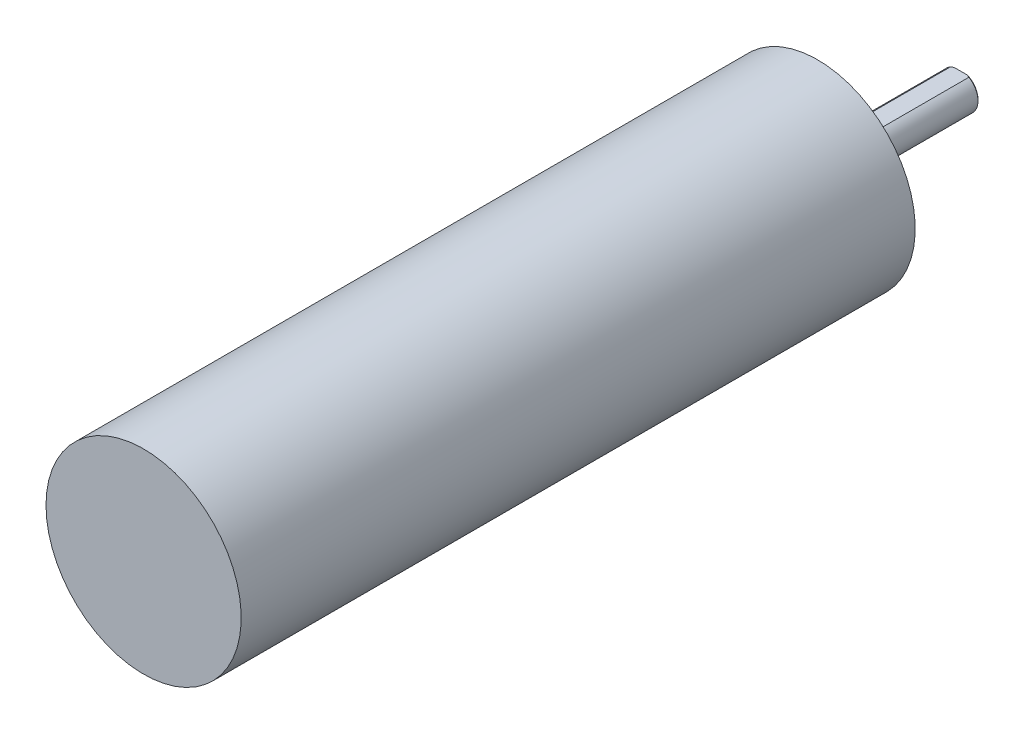
SolidWorks part; units mm, degrees
ref_plane "前视基准面" through (0, 0, 0) normal (0, 0, 1) x (1, 0, 0)
ref_plane "上视基准面" through (0, 0, 0) normal (0, 1, 0) x (1, 0, 0)
ref_plane "右视基准面" through (0, 0, 0) normal (1, 0, 0) x (0, 0, -1)
sketch "草图1" plane through (0, 0, 0) normal (0, 0, 1) x (1, 0, 0)
  circle A0 centre (0, 0) radius 8
  dimension "D1" = 16
extrude "拉伸1" add sketch "草图1" along normal blind 55.2
sketch "草图2" plane through (0, 0, 0) normal (0, 0, -1) x (-1, 0, 0)
  line L0 (-0.7483, 1.3) -> (0.7483, 1.3)
  arc A0 (-0.7483, 1.3) -> (0.7483, 1.3) centre (0, 0) ccw
  dimension "D1" = 3
  dimension "D2" = 1.3
extrude "拉伸2" add sketch "草图2" along normal blind 11.8
sketch "草图3" plane through (0, 0, 0) normal (0, 0, -1) x (-1, 0, 0)
  circle A0 centre (0, 0) radius 3
  dimension "D1" = 6
extrude "拉伸3" add sketch "草图3" along normal blind 1
sketch "草图4" plane through (0, 0, -1) normal (0, 0, -1) x (-1, 0, 0)
  circle A0 centre (0, 0) radius 2.75
  dimension "D1" = 5.5
extrude "拉伸4" add sketch "草图4" along normal blind 1.6
sketch "草图5" plane through (0, 0, 0) normal (0, 0, -1) x (-1, 0, 0)
  circle A0 centre (0, 0) radius 8
  dimension "D1" = 16
extrude "拉伸5" add sketch "草图5" against normal blind 2 and the other way blind 0.05
sketch "草图6" plane through (0, 0, -11.8) normal (0, 0, -1) x (-1, 0, 0)
  point P0 (0, 0)
sketch "草图7" plane through (0, 0, -0.05) normal (0, 0, -1) x (-1, 0, 0)
  line L0 (-5.5, 0) -> (5.5, 0)
  dimension "D1" = 11
hole_wizard "M2 螺纹孔1" positions "3D草图1" profile "草图8" tap size "M2" standard "GB"
sketch3d "3D草图1"
  point P0 (5.5, 0, -0.05)
  point P3 (-5.5, 0, -0.05)
sketch "草图8" plane through (5.5, 0, -0.05) normal (1, 0, 0) x (0, 1, 0)
  line L0 (0, 0) -> (0, 5.6807)
  line L1 (0, 5.6807) -> (0.8, 5.2)
  line L2 (0.8, 5.2) -> (0.8, 0)
  line L5 (0.8, 0) -> (0, 0)
  line L10 (0, 5.6807) -> (-0.8, 5.2) construction
  line L11 (0, -6.35) -> (0, 107.95) construction
  dimension "螺纹孔钻头直径" = 1.6
  dimension "螺纹孔钻头深度" = 5.2
  dimension "导头角度" = 118
cosmetic thread "孔螺蚊线1" parameters "D1"=4, "D2"=2
cosmetic thread "孔螺蚊线2" parameters "D1"=4, "D2"=2
sketch "Sketch1" plane through (0, 0, -2.6) normal (0, 0, -1) x (-1, 0, 0)
  circle A0 centre (0, 0) radius 1.5
  dimension "D1" = 3
extrude "Extrude1" add sketch "Sketch1" along normal blind 1.4
sketch "Sketch2" plane through (0, 0, 55.2) normal (0, 0, 1) x (1, 0, 0)
  line L0 (0, 0) -> (3.8389, -3.8389) construction
  line L1 (0, 0) -> (5.429, 0) construction
  line L2 (0, 0) -> (3.8389, 3.8389) construction
  arc A0 (3.8389, -3.8389) -> (3.8389, 3.8389) centre (0, 0) ccw construction
  arc A1 (4.7935, -4.7935) -> (4.7935, 4.7935) centre (0, 0) ccw
  arc A2 (2.8843, -2.8843) -> (2.8843, 2.8843) centre (0, 0) ccw
  arc A3 (2.8843, -2.8843) -> (4.7935, -4.7935) centre (3.8389, -3.8389) ccw
  arc A4 (4.7935, 4.7935) -> (2.8843, 2.8843) centre (3.8389, 3.8389) ccw
  point P4 (5.429, 0)
  dimension "D2" = 1.35
  dimension "D1" = 45
extrude "Extrude2" [suppressed] add sketch "Sketch2" along normal blind 115
chamfer "倒角2" distance 0.1 angle 45 1 edges at (0, -1.5, -11.8)
